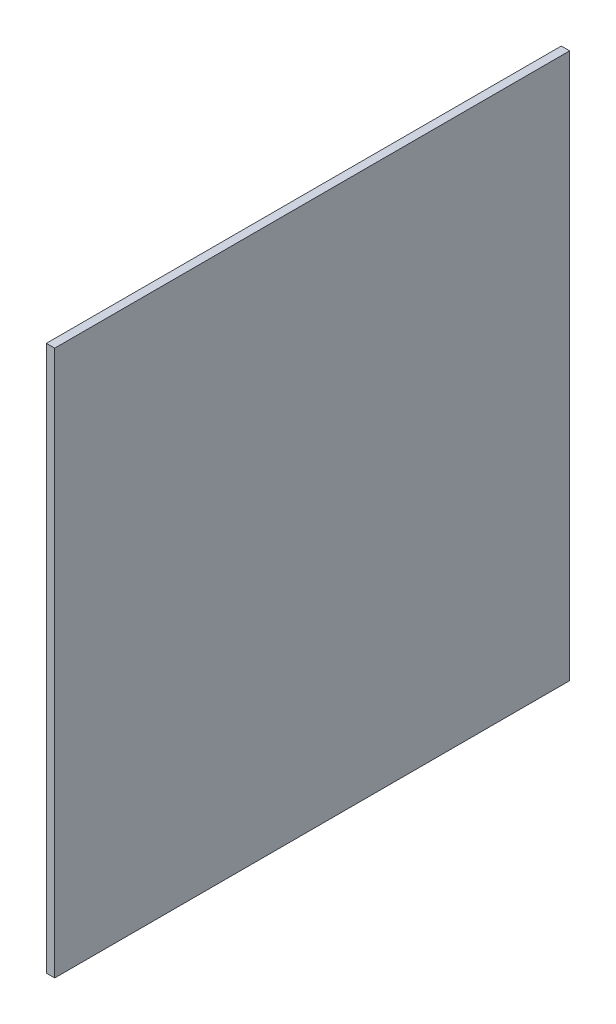
SolidWorks part; units mm, degrees
ref_plane "Спереди" through (0, 0, 0) normal (0, 0, 1) x (1, 0, 0)
ref_plane "Сверху" through (0, 0, 0) normal (0, 1, 0) x (1, 0, 0)
ref_plane "Справа" through (0, 0, 0) normal (1, 0, 0) x (0, 0, -1)
sketch "Эскиз1" plane through (0, 0, 0) normal (1, 0, 0) x (0, 0, -1)
  line L0 (57.9265, 0) -> (57.9265, -260.902)
  line L1 (-188.3871, 0) -> (57.9265, 0)
  line L2 (-188.3871, 0) -> (-188.3871, -260.902)
  line L3 (-188.3871, -260.902) -> (57.9265, -260.902)
extrude "Вытянуть1" add sketch "Эскиз1" along normal blind 4
